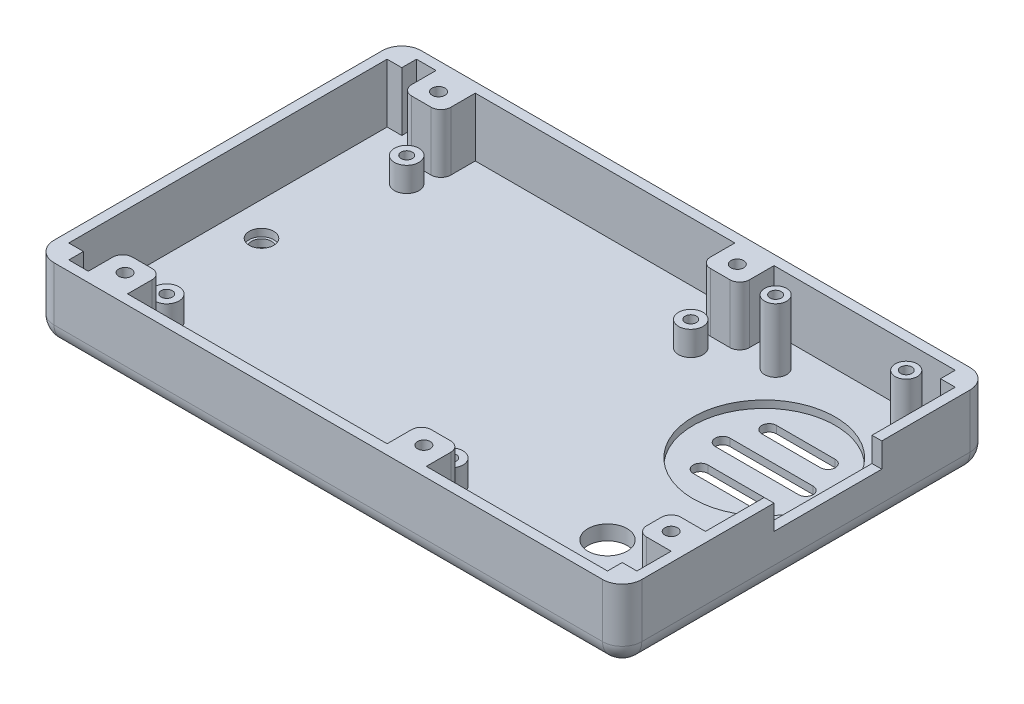
SolidWorks part; units mm, degrees
ref_plane "Front Plane" through (0, 0, 0) normal (0, 0, 1) x (1, 0, 0)
ref_plane "Top Plane" through (0, 0, 0) normal (0, 1, 0) x (1, 0, 0)
ref_plane "Right Plane" through (0, 0, 0) normal (1, 0, 0) x (0, 0, -1)
sketch "Sketch1" plane through (0, 0, 0) normal (0, 1, 0) x (1, 0, 0)
  line L1 (-60, 37.5) -> (60, 37.5)
  line L2 (-60, 37.5) -> (-60, -37.5)
  line L3 (-60, -37.5) -> (60, -37.5)
  line L4 (60, 37.5) -> (60, -37.5)
  line L5 (-60, 37.5) -> (60, -37.5) construction
  line L6 (-60, -37.5) -> (60, 37.5) construction
  point P0 (0, 0)
  dimension "D1" = 120
  dimension "D2" = 75
extrude "Main Structure" add sketch "Sketch1" along normal blind 15
sketch "Sketch2" plane through (0, 15, 0) normal (0, 1, 0) x (1, 0, 0)
  line L1 (-58, -35.5) -> (58, -35.5)
  line L2 (-58, -35.5) -> (-58, 35.5)
  line L3 (-58, 35.5) -> (58, 35.5)
  line L4 (58, -35.5) -> (58, 35.5)
  line L5 (-58, -35.5) -> (58, 35.5) construction
  line L6 (-58, 35.5) -> (58, -35.5) construction
  point P0 (0, 0)
  dimension "D1" = 71
  dimension "D2" = 116
extrude "Inside Cut" cut sketch "Sketch2" against normal blind 12
sketch "Sketch3" plane through (0, 3, 0) normal (0, 1, 0) x (1, 0, 0)
  line L0 (-58, 35.5) -> (-58, -35.5) construction
  line L1 (-58, -35.5) -> (58, -35.5) construction
  line L2 (58, 35.5) -> (-58, 35.5) construction
  circle A0 centre (-46, -24.5) radius 2.5
  circle A1 centre (-46, 24.5) radius 2.5
  circle A2 centre (-46, 24.5) radius 1.15
  circle A3 centre (-46, -24.5) radius 1.15
  circle A4 centre (12, 24.5) radius 2.5
  circle A5 centre (12, -24.5) radius 2.5
  circle A6 centre (12, 24.5) radius 1.15
  circle A7 centre (12, -24.5) radius 1.15
  dimension "D1" = 5
  dimension "D3" = 5
  dimension "D7" = 2.3
  dimension "D8" = 2.3
  dimension "D9" = 5
  dimension "D10" = 5
  dimension "D15" = 2.3
  dimension "D16" = 2.3
  dimension "D2" = 12
  dimension "D4" = 12
  dimension "D5" = 11
  dimension "D6" = 11
  dimension "D11" = 11
  dimension "D12" = 58
  dimension "D13" = 58
  dimension "D14" = 11
extrude "Pi Standoffs" add sketch "Sketch3" along normal blind 5
sketch "Sketch4" plane through (0, 3, 0) normal (0, 1, 0) x (1, 0, 0)
  line L0 (58, -35.5) -> (58, 35.5) construction
  line L1 (-58, -35.5) -> (58, -35.5) construction
  circle A0 centre (48, -30.5) radius 2
  circle A1 centre (48, -17.5) radius 2
  circle A2 centre (48, -17.5) radius 0.9
  circle A3 centre (48, -30.5) radius 0.9
  dimension "D1" = 4
  dimension "D4" = 4
  dimension "D6" = 1.8
  dimension "D7" = 1.8
  dimension "D2" = 10
  dimension "D3" = 5
  dimension "D5" = 13
extrude "Camera Standoffs" add sketch "Sketch4" along normal blind 5
fillet "Body Fillet 1" radius 4 1 edges at (-60, 0, 0)
fillet "Body Fillet 2" radius 4 3 edges at (-60, 9.5, -37.5) (-58.8284, 1.1716, -37.5) (2, 0, -37.5)
fillet "Body Fillet 3" radius 4 3 edges at (-60, 9.5, 37.5) (-58.8284, 1.1716, 37.5) (2, 0, 37.5)
fillet "Body Fillet 4" radius 4 5 edges at (60, 9.5, 37.5) (60, 1.1716, 36.3284) (60, 9.5, -37.5) (60, 1.1716, -36.3284) (60, 0, 0)
sketch "Sketch5" plane through (0, 3, 0) normal (0, 1, 0) x (1, 0, 0)
  line L0 (58, 35.5) -> (-58, 35.5) construction
  line L1 (58, -35.5) -> (58, 35.5) construction
  circle A0 centre (24.33, 29.5) radius 2.25
  circle A1 centre (51, 29.5) radius 2.25
  circle A2 centre (51, 29.5) radius 1.15
  circle A4 centre (24.33, 29.5) radius 1.15
  dimension "D1" = 4.5
  dimension "D3" = 4.5
  dimension "D6" = 2.3
  dimension "D7" = 2.3
  dimension "D2" = 6
  dimension "D4" = 7
  dimension "D5" = 26.67
extrude "Fona Standoffs" add sketch "Sketch5" along normal blind 13
sketch "Sketch6" plane through (0, 3, 0) normal (0, 1, 0) x (1, 0, 0)
  line L1 (-58, -35.5) -> (-55, -35.5)
  line L2 (-58, -35.5) -> (-58, -32.5)
  line L3 (-58, -32.5) -> (-55, -32.5)
  line L4 (-55, -35.5) -> (-55, -32.5)
  line L5 (-58, 35.5) -> (-55, 35.5)
  line L6 (-58, 35.5) -> (-58, 32.5)
  line L7 (-58, 32.5) -> (-55, 32.5)
  line L8 (-55, 35.5) -> (-55, 32.5)
  line L9 (58, -35.5) -> (55, -35.5)
  line L10 (58, -35.5) -> (58, -32.5)
  line L11 (58, -32.5) -> (55, -32.5)
  line L12 (55, -35.5) -> (55, -32.5)
  line L13 (58, 35.5) -> (55, 35.5)
  line L14 (58, 35.5) -> (58, 32.5)
  line L15 (58, 32.5) -> (55, 32.5)
  line L16 (55, 35.5) -> (55, 32.5)
  dimension "D1" = 3
  dimension "D2" = 3
  dimension "D3" = 3
  dimension "D4" = 3
  dimension "D5" = 3
  dimension "D6" = 3
  dimension "D7" = 3
  dimension "D8" = 3
extrude "Corner Support" add sketch "Sketch6" along normal blind 12
sketch "Sketch8" plane through (60, 0, 0) normal (1, 0, 0) x (0, 0, -1)
  line L0 (-33.5, 15) -> (-33.5, 4) construction
  line L1 (-6.5, 15) -> (15.5, 15)
  line L2 (-6.5, 15) -> (-6.5, 10)
  line L3 (-6.5, 10) -> (15.5, 10)
  line L4 (15.5, 15) -> (15.5, 10)
  line L5 (-6.5, 15) -> (15.5, 10) construction
  line L6 (-6.5, 10) -> (15.5, 15) construction
  line L7 (-33.5, 4) -> (33.5, 4) construction
  line L8 (-33.5, 15) -> (33.5, 15) construction
  point P0 (4.5, 12.5)
  dimension "D1" = 27
  dimension "D2" = 6
  dimension "D3" = 0
  dimension "D4" = 22
extrude "Charger Cutout" cut sketch "Sketch8" against normal blind 10
sketch "Sketch9" plane through (0, 3, 0) normal (0, 1, 0) x (1, 0, 0)
  line L1 (-51, -28.5) -> (-43, -28.5)
  line L2 (-51, -28.5) -> (-51, -35.5)
  line L3 (-51, -35.5) -> (-43, -35.5)
  line L4 (-43, -28.5) -> (-43, -35.5)
  line L5 (-51, -28.5) -> (-43, -35.5) construction
  line L6 (-51, -35.5) -> (-43, -28.5) construction
  line L7 (-55, -35.5) -> (55, -35.5) construction
  line L8 (51, -18.5) -> (58, -18.5)
  line L9 (-51, 35.5) -> (-43, 35.5)
  line L10 (-51, 35.5) -> (-51, 28.5)
  line L11 (-51, 28.5) -> (-43, 28.5)
  line L12 (-43, 35.5) -> (-43, 28.5)
  line L13 (-51, 35.5) -> (-43, 28.5) construction
  line L14 (-51, 28.5) -> (-43, 35.5) construction
  line L15 (55, 35.5) -> (-55, 35.5) construction
  line L16 (-58, 32.5) -> (-58, -32.5) construction
  line L17 (58, -32.5) -> (58, 32.5) construction
  line L18 (10, 35.5) -> (18, 35.5)
  line L19 (10, 35.5) -> (10, 28.5)
  line L20 (10, 28.5) -> (18, 28.5)
  line L21 (18, 35.5) -> (18, 28.5)
  line L22 (10, 35.5) -> (18, 28.5) construction
  line L23 (10, 28.5) -> (18, 35.5) construction
  line L24 (51, -18.5) -> (51, -25.5)
  line L25 (10, -28.5) -> (18, -28.5)
  line L26 (10, -28.5) -> (10, -35.5)
  line L27 (10, -35.5) -> (18, -35.5)
  line L28 (18, -28.5) -> (18, -35.5)
  line L29 (10, -28.5) -> (18, -35.5) construction
  line L30 (10, -35.5) -> (18, -28.5) construction
  line L31 (51, -25.5) -> (58, -25.5)
  line L32 (58, -18.5) -> (58, -25.5)
  line L33 (51, -18.5) -> (58, -25.5) construction
  line L34 (51, -25.5) -> (58, -18.5) construction
  point P0 (-47, -32)
  point P9 (54.5, -22)
  point P11 (-47, 32)
  point P16 (14, 32)
  point P29 (14, -32)
  dimension "D5" = 0
  dimension "D10" = 7
  dimension "D16" = 10
  dimension "D2" = 0
  dimension "D3" = 7
  dimension "D4" = 8
  dimension "D6" = 8
  dimension "D7" = 7
  dimension "D8" = 7
  dimension "D9" = 0
  dimension "D11" = 7
  dimension "D12" = 7
  dimension "D13" = 8
  dimension "D14" = 0
  dimension "D15" = 40
  dimension "D17" = 8
  dimension "D18" = 7
  dimension "D19" = 40
  dimension "D20" = 0
extrude "Mounting Structure" add sketch "Sketch9" along normal blind 12
fillet "Mounting Structure Fillet" radius 2 10 edges at (-43, 9, -28.5) (-51, 9, -28.5) (10, 9, -28.5) (18, 9, -28.5) (10, 9, 28.5) (18, 9, 28.5) (-51, 9, 28.5) (-43, 9, 28.5) (51, 9, 18.5) (51, 9, 25.5)
sketch "Sketch10" plane through (0, 15, 0) normal (0, 1, 0) x (1, 0, 0)
  line L0 (-51, 35.5) -> (-51, 30.5) construction
  line L1 (-49, 28.5) -> (-45, 28.5) construction
  line L2 (-51, -30.5) -> (-51, -35.5) construction
  line L3 (-45, -28.5) -> (-49, -28.5) construction
  line L4 (10, -30.5) -> (10, -35.5) construction
  line L5 (16, -28.5) -> (12, -28.5) construction
  line L6 (12, 28.5) -> (16, 28.5) construction
  line L7 (10, 35.5) -> (10, 30.5) construction
  line L8 (51, -20.5) -> (51, -23.5) construction
  line L9 (53, -25.5) -> (58, -25.5) construction
  circle A0 centre (-47, 32) radius 1.3
  circle A1 centre (-47, -32) radius 1.3
  circle A2 centre (14, -32) radius 1.3
  circle A3 centre (14, 32) radius 1.3
  circle A4 centre (54.5, -22) radius 1.3
  point P10 (-47, -28.5)
  dimension "D1" = 2.6
  dimension "D4" = 2.6
  dimension "D7" = 2.6
  dimension "D10" = 2.6
  dimension "D13" = 2.6
  dimension "D2" = 4
  dimension "D3" = 3.5
  dimension "D5" = 4
  dimension "D6" = 3.5
  dimension "D8" = 4
  dimension "D9" = 3.5
  dimension "D11" = 3.5
  dimension "D12" = 4
  dimension "D14" = 3.5
  dimension "D15" = 3.5
extrude "Case Mounting Holes" cut sketch "Sketch10" against normal blind 15
sketch "Sketch13" plane through (0, 0, 0) normal (0, -1, 0) x (1, 0, 0)
  circle A0 centre (-47, 32) radius 2.9
  circle A1 centre (14, 32) radius 2.9
  circle A2 centre (14, -32) radius 2.9
  circle A3 centre (-47, -32) radius 2.9
  circle A4 centre (54.5, 22) radius 2.9
  dimension "D1" = 5.8
  dimension "D2" = 5.8
  dimension "D3" = 5.8
  dimension "D4" = 5.8
  dimension "D5" = 5.8
extrude "Case Screw Head Holes" cut sketch "Sketch13" against normal blind 8.85
sketch "Sketch14" plane through (0, 3, 0) normal (0, 1, 0) x (1, 0, 0)
  line L0 (55, 35.5) -> (18, 35.5) construction
  line L1 (58, -32.5) -> (58, -25.5) construction
  circle A0 centre (39, 12.5) radius 14.5
  dimension "D1" = 29
  dimension "D2" = 23
  dimension "D3" = 19
extrude "Speaker Holder" cut sketch "Sketch14" against normal blind 1.5
sketch "Sketch23" plane through (0, 1.5, 0) normal (0, 1, 0) x (1, 0, 0)
  line L0 (33, 19.5) -> (45, 19.5) construction
  line L1 (33, 21) -> (45, 21)
  line L2 (33, 18) -> (45, 18)
  line L3 (30.5, 12.5) -> (47.5, 12.5) construction
  line L4 (30.5, 14) -> (47.5, 14)
  line L5 (30.5, 11) -> (47.5, 11)
  line L6 (33, 5.5) -> (45, 5.5) construction
  line L7 (33, 7) -> (45, 7)
  line L8 (33, 4) -> (45, 4)
  arc A0 (33, 21) -> (33, 18) centre (33, 19.5) ccw
  arc A1 (45, 18) -> (45, 21) centre (45, 19.5) ccw
  circle A2 centre (39, 12.5) radius 14.5 construction
  arc A3 (30.5, 14) -> (30.5, 11) centre (30.5, 12.5) ccw
  arc A4 (47.5, 11) -> (47.5, 14) centre (47.5, 12.5) ccw
  arc A5 (33, 7) -> (33, 4) centre (33, 5.5) ccw
  arc A6 (45, 4) -> (45, 7) centre (45, 5.5) ccw
  point P2 (39, 19.5)
  point P11 (39, 12.5)
  point P19 (39, 5.5)
  dimension "D3" = 7
  dimension "D1" = 3
  dimension "D2" = 15
  dimension "D4" = 3
  dimension "D5" = 20
  dimension "D6" = 3
  dimension "D7" = 15
  dimension "D8" = 7
extrude "Sound Cutout" cut sketch "Sketch23" against normal blind 1.5
sketch "Sketch25" plane through (0, 3, 0) normal (0, 1, 0) x (1, 0, 0)
  circle A0 centre (-51.1477, 0) radius 2.5
  dimension "D1" = 5
extrude "Microphone holder" cut sketch "Sketch25" against normal blind 1.5
sketch "Sketch26" plane through (0, 1.5, 0) normal (0, 1, 0) x (1, 0, 0)
  circle A0 centre (-51.1477, 0) radius 2
  dimension "D1" = 4
extrude "Microphone Cutout" cut sketch "Sketch26" against normal blind 1.5
sketch "Sketch27" plane through (0, 3, 0) normal (0, 1, 0) x (1, 0, 0)
  line L0 (-58, 32.5) -> (-58, -32.5) construction
  line L1 (55, 35.5) -> (18, 35.5) construction
  circle A0 centre (37.5, -18) radius 4
  dimension "D1" = 8
  dimension "D2" = 95.5
  dimension "D3" = 53.5
extrude "Camera Cutout" cut sketch "Sketch27" against normal blind 10
